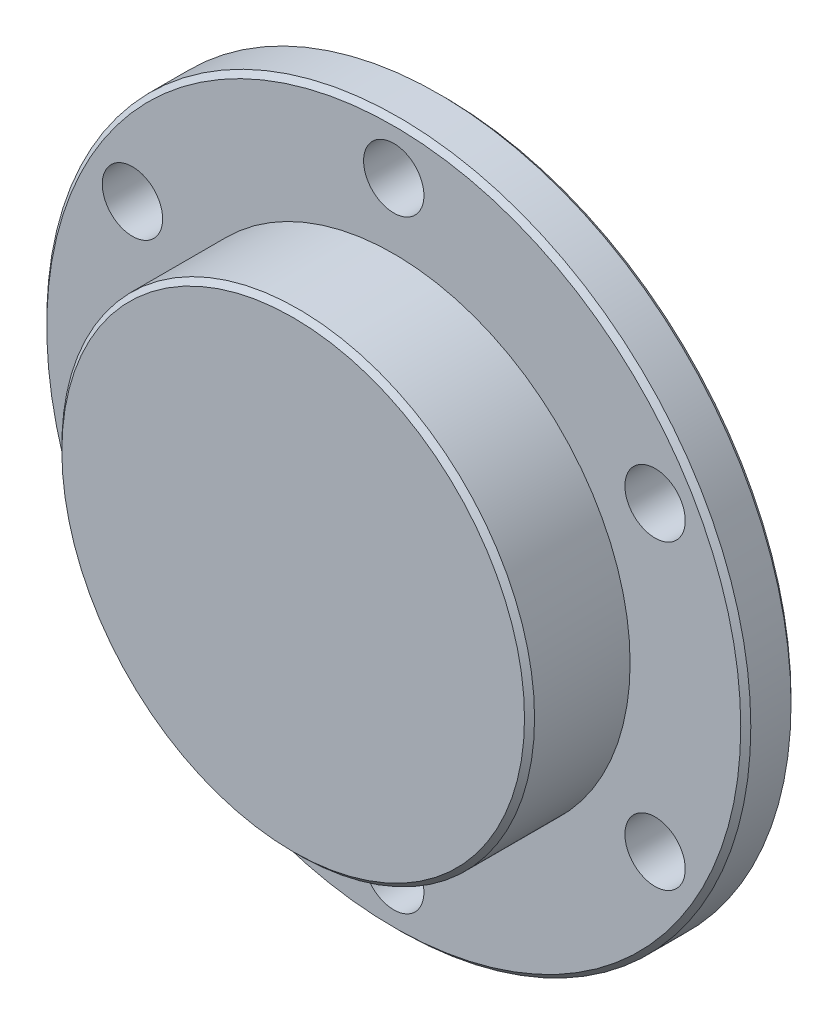
SolidWorks part; units mm, degrees
ref_plane "前视基准面" through (0, 0, 0) normal (0, 0, 1) x (1, 0, 0)
ref_plane "上视基准面" through (0, 0, 0) normal (0, 1, 0) x (1, 0, 0)
ref_plane "右视基准面" through (0, 0, 0) normal (1, 0, 0) x (0, 0, -1)
sketch "草图1" plane through (0, 0, 0) normal (0, 0, 1) x (1, 0, 0)
  circle A0 centre (0, 0) radius 35
extrude "拉伸1" add sketch "草图1" along normal blind 5
sketch "草图2" plane through (0, 0, 5) normal (0, 0, 1) x (1, 0, 0)
  circle A0 centre (0, 0) radius 23.5
extrude "拉伸2" add sketch "草图2" along normal blind 10
sketch "草图3" plane through (0, 0, 0) normal (0, 0, -1) x (-1, 0, 0)
  circle A0 centre (0, 0) radius 20
extrude "切除-拉伸1" cut sketch "草图3" against normal blind 12
sketch "草图4" plane through (0, 0, 5) normal (0, 0, 1) x (1, 0, 0)
  circle A0 centre (25.9808, 15) radius 3
  circle A1 centre (0, 30) radius 3
  circle A2 centre (25.9808, -15) radius 3
  circle A3 centre (0, -30) radius 3
  circle A4 centre (-25.9808, -15) radius 3
  circle A5 centre (-25.9808, 15) radius 3
extrude "切除-拉伸2" cut sketch "草图4" against normal blind 12
chamfer "倒角1" distance 0.5 angle 45 4 edges at (-20, 0, 0) (35, 0, 0) (35, 0, 5) (23.5, 0, 15)
